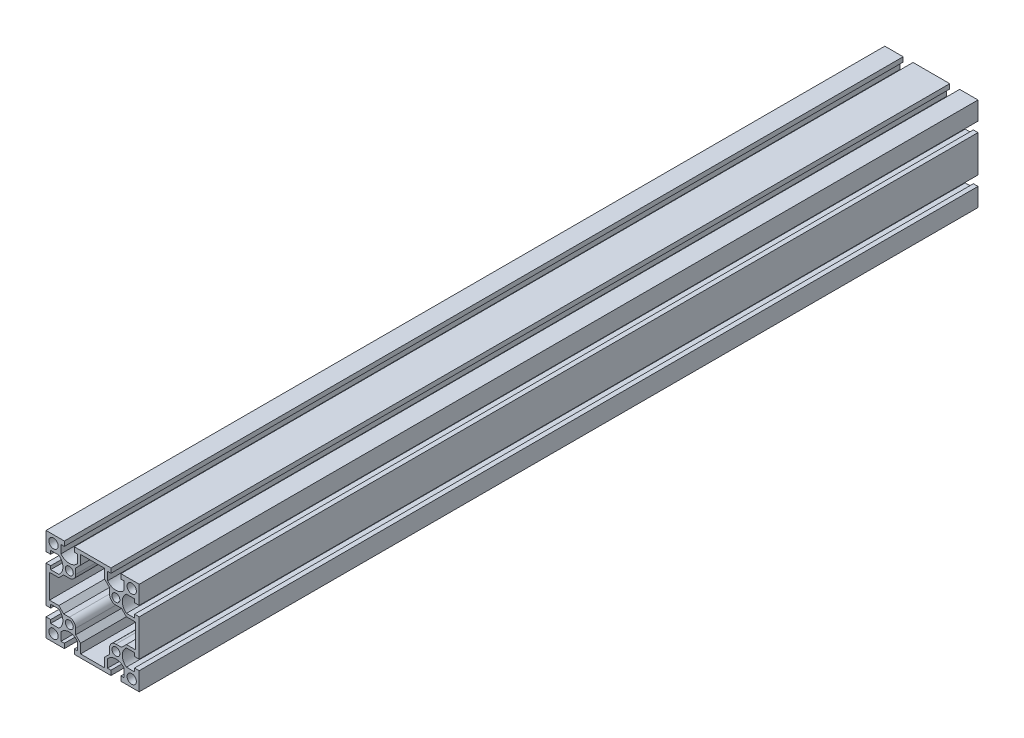
SolidWorks part; units mm, degrees
ref_plane "前视基准面" through (0, 0, 0) normal (0, 0, 1) x (1, 0, 0)
ref_plane "上视基准面" through (0, 0, 0) normal (0, 1, 0) x (1, 0, 0)
ref_plane "右视基准面" through (0, 0, 0) normal (1, 0, 0) x (0, 0, -1)
other "Configuration Table"
sketch "草图1" plane through (0, 0, 0) normal (0, 0, 1) x (1, 0, 0)
  line L0 (0, 0) -> (0, 50.1573) construction
  line L1 (0, 0) -> (-73.5163, 0) construction
  line L2 (0, 0) -> (-54.4301, 54.4301) construction
  line L3 (-40, 40) -> (-24.25, 40)
  line L4 (-40, 40) -> (-40, 24.25) construction
  line L7 (-24.25, 40) -> (-24.25, 36)
  line L8 (-24.25, 36) -> (-27.15, 36)
  line L9 (-27.15, 36) -> (-27.15, 29)
  line L10 (-15.75, 40) -> (-15.75, 36)
  line L11 (-15.75, 36) -> (-12.85, 36)
  line L12 (-12.85, 36) -> (-12.85, 29)
  line L13 (10.35, 37) -> (-10.35, 37)
  line L14 (-10.35, 37) -> (-10.35, 29)
  line L15 (-20, 46.3565) -> (-20, 13.3226) construction
  line L16 (-22.6887, 25.5) -> (-15.1183, 25.5) construction
  line L17 (-10.35, 29) -> (-14.5, 24.85)
  line L18 (-14.5, 24.85) -> (-14.5, 20)
  line L19 (-33.575, 44.626) -> (-33.575, 38.1973) construction
  line L20 (-44.626, 33.575) -> (-38.1973, 33.575) construction
  line L21 (-25.5, 22.6887) -> (-25.5, 5.6618) construction
  line L22 (-43.4182, 20) -> (-13.3226, 20) construction
  line L23 (-24.85, 14.5) -> (-20, 14.5)
  line L24 (-29, 10.35) -> (-24.85, 14.5)
  line L25 (-37, 10.35) -> (-29, 10.35)
  line L26 (-37, -10.35) -> (-37, 10.35)
  line L27 (-36, 12.85) -> (-29, 12.85)
  line L28 (-36, 15.75) -> (-36, 12.85)
  line L29 (-40.0003, 15.75) -> (-36, 15.75)
  line L30 (-36, 27.15) -> (-29, 27.15)
  line L31 (-36, 24.25) -> (-36, 27.15)
  line L32 (-40, 24.25) -> (-36, 24.25)
  line L33 (-40, 40) -> (-40, 24.25)
  line L34 (46.3565, 20) -> (13.3226, 20) construction
  line L35 (25.5, 22.6887) -> (25.5, 5.6618) construction
  line L36 (44.626, 33.575) -> (38.1973, 33.575) construction
  line L37 (33.575, 44.626) -> (33.575, 38.1973) construction
  line L38 (22.6887, 25.5) -> (15.1183, 25.5) construction
  line L39 (20, 46.3565) -> (20, 13.3226) construction
  line L40 (40, 40) -> (40, 24.25) construction
  line L41 (40, 40) -> (40, 24.25)
  line L42 (40, 24.25) -> (36, 24.25)
  line L43 (36, 24.25) -> (36, 27.15)
  line L44 (36, 27.15) -> (29, 27.15)
  line L45 (40.0003, 15.75) -> (36, 15.75)
  line L46 (36, 15.75) -> (36, 12.85)
  line L47 (36, 12.85) -> (29, 12.85)
  line L48 (37, -10.35) -> (37, 10.35)
  line L49 (37, 10.35) -> (29, 10.35)
  line L50 (29, 10.35) -> (24.85, 14.5)
  line L51 (24.85, 14.5) -> (20, 14.5)
  line L52 (14.5, 24.85) -> (14.5, 20)
  line L53 (10.35, 29) -> (14.5, 24.85)
  line L54 (10.35, 37) -> (10.35, 29)
  line L55 (12.85, 36) -> (12.85, 29)
  line L56 (15.75, 36) -> (12.85, 36)
  line L57 (15.75, 40) -> (15.75, 36)
  line L58 (27.15, 36) -> (27.15, 29)
  line L59 (24.25, 36) -> (27.15, 36)
  line L60 (24.25, 40) -> (24.25, 36)
  line L61 (22.6887, -25.5) -> (15.1183, -25.5) construction
  line L62 (44.626, -33.575) -> (38.1973, -33.575) construction
  line L63 (25.5, -22.6887) -> (25.5, -5.6618) construction
  line L64 (46.3565, -20) -> (13.3226, -20) construction
  line L65 (-46.3565, -20) -> (-13.3226, -20) construction
  line L66 (-25.5, -22.6887) -> (-25.5, -5.6618) construction
  line L67 (-44.626, -33.575) -> (-38.1973, -33.575) construction
  line L68 (-22.6887, -25.5) -> (-15.1183, -25.5) construction
  line L69 (24.25, -40) -> (24.25, -36)
  line L70 (24.25, -36) -> (27.15, -36)
  line L71 (27.15, -36) -> (27.15, -29)
  line L72 (15.75, -40) -> (15.75, -36)
  line L73 (15.75, -36) -> (12.85, -36)
  line L74 (12.85, -36) -> (12.85, -29)
  line L75 (10.35, -37) -> (10.35, -29)
  line L76 (10.35, -29) -> (14.5, -24.85)
  line L77 (14.5, -24.85) -> (14.5, -20)
  line L78 (24.85, -14.5) -> (20, -14.5)
  line L79 (29, -10.35) -> (24.85, -14.5)
  line L80 (37, -10.35) -> (29, -10.35)
  line L81 (36, -12.85) -> (29, -12.85)
  line L82 (36, -15.75) -> (36, -12.85)
  line L83 (40.0003, -15.75) -> (36, -15.75)
  line L84 (36, -27.15) -> (29, -27.15)
  line L85 (36, -24.25) -> (36, -27.15)
  line L86 (40, -24.25) -> (36, -24.25)
  line L87 (-40, -24.25) -> (-36, -24.25)
  line L88 (-36, -24.25) -> (-36, -27.15)
  line L89 (-36, -27.15) -> (-29, -27.15)
  line L90 (-40.0003, -15.75) -> (-36, -15.75)
  line L91 (-36, -15.75) -> (-36, -12.85)
  line L92 (-36, -12.85) -> (-29, -12.85)
  line L93 (-37, -10.35) -> (-29, -10.35)
  line L94 (-29, -10.35) -> (-24.85, -14.5)
  line L95 (-24.85, -14.5) -> (-20, -14.5)
  line L96 (-14.5, -24.85) -> (-14.5, -20)
  line L97 (-10.35, -29) -> (-14.5, -24.85)
  line L98 (-10.35, -37) -> (-10.35, -29)
  line L99 (10.35, -37) -> (-10.35, -37)
  line L100 (-12.85, -36) -> (-12.85, -29)
  line L101 (-15.75, -36) -> (-12.85, -36)
  line L102 (-15.75, -40) -> (-15.75, -36)
  line L103 (-27.15, -36) -> (-27.15, -29)
  line L104 (-24.25, -36) -> (-27.15, -36)
  line L105 (-24.25, -40) -> (-24.25, -36)
  line L106 (-40, -40) -> (-24.25, -40)
  line L107 (40, -24.25) -> (40, -40) construction
  line L108 (40, -24.25) -> (40, -40)
  line L109 (24.25, -40) -> (40, -40)
  line L110 (-15.75, -40) -> (15.75, -40)
  line L111 (-40, 15.75) -> (-40, -15.75) construction
  line L112 (-40, 15.75) -> (-40, -15.75)
  line L113 (24.25, 40) -> (40, 40)
  line L114 (40, 15.75) -> (40, -15.75) construction
  line L115 (40, 15.75) -> (40, -15.75)
  line L116 (-40, -24.25) -> (-40, -40) construction
  line L117 (-40, -24.25) -> (-40, -40)
  line L118 (-15.75, 40) -> (15.75, 40)
  arc A0 (-27.15, 29) -> (-12.85, 29) centre (-20, 34.5532) ccw
  circle A1 centre (-20, 20) radius 3.4
  arc A2 (-20, 14.5) -> (-14.5, 20) centre (-20, 20) ccw
  circle A3 centre (-33.575, 33.575) radius 4
  arc A4 (-29, 27.15) -> (-29, 12.85) centre (-34.5532, 20) cw
  arc A5 (29, 27.15) -> (29, 12.85) centre (34.5532, 20) ccw
  circle A6 centre (33.575, 33.575) radius 4
  arc A7 (20, 14.5) -> (14.5, 20) centre (20, 20) cw
  circle A8 centre (20, 20) radius 3.4
  arc A9 (27.15, 29) -> (12.85, 29) centre (20, 34.5532) cw
  arc A10 (27.15, -29) -> (12.85, -29) centre (20, -34.5532) ccw
  circle A11 centre (20, -20) radius 3.4
  arc A12 (20, -14.5) -> (14.5, -20) centre (20, -20) ccw
  circle A13 centre (33.575, -33.575) radius 4
  arc A14 (29, -27.15) -> (29, -12.85) centre (34.5532, -20) cw
  arc A15 (-29, -27.15) -> (-29, -12.85) centre (-34.5532, -20) ccw
  circle A16 centre (-33.575, -33.575) radius 4
  arc A17 (-20, -14.5) -> (-14.5, -20) centre (-20, -20) cw
  circle A18 centre (-20, -20) radius 3.4
  arc A19 (-27.15, -29) -> (-12.85, -29) centre (-20, -34.5532) cw
  point P66 (-40, 0)
  point P92 (0, 37)
  point P98 (0, 40)
  point P152 (37, 0)
  point P158 (40, 0)
  point P165 (-37, 0)
  point P176 (0, -40)
  point P177 (0, -37)
  dimension "D12" = 6.8
  dimension "D13" = 11
  dimension "D15" = 8
  dimension "D18" = 80
  dimension "D1" = 40
  dimension "D2" = 40
  dimension "D3" = 45
  dimension "D4" = 20
  dimension "D5" = 8.5
  dimension "D6" = 4
  dimension "D7" = 3
  dimension "D8" = 11
  dimension "D9" = 14.3
  dimension "D10" = 14.5
  dimension "D11" = 2.5
  dimension "D14" = 45
  dimension "D16" = 3
  dimension "D17" = 45
  dimension "D19" = 80
extrude "凸台-拉伸1" add sketch "草图1" along normal mid plane 720 contours L103 A19 L100 L101 L102 L110 L72 L73 L74 A10 L71 L70 L69 L109 L108 L86 L85 L84 A14 L81 L82 L83 L115 L45 L46 L47 A5 L44 L43 L42 L41 L113 L60 L59 L58 A9 L55 L56 L57 L118 L10 L11 L12 A0 L9 L8 L7 L3 L33 L32 L31
